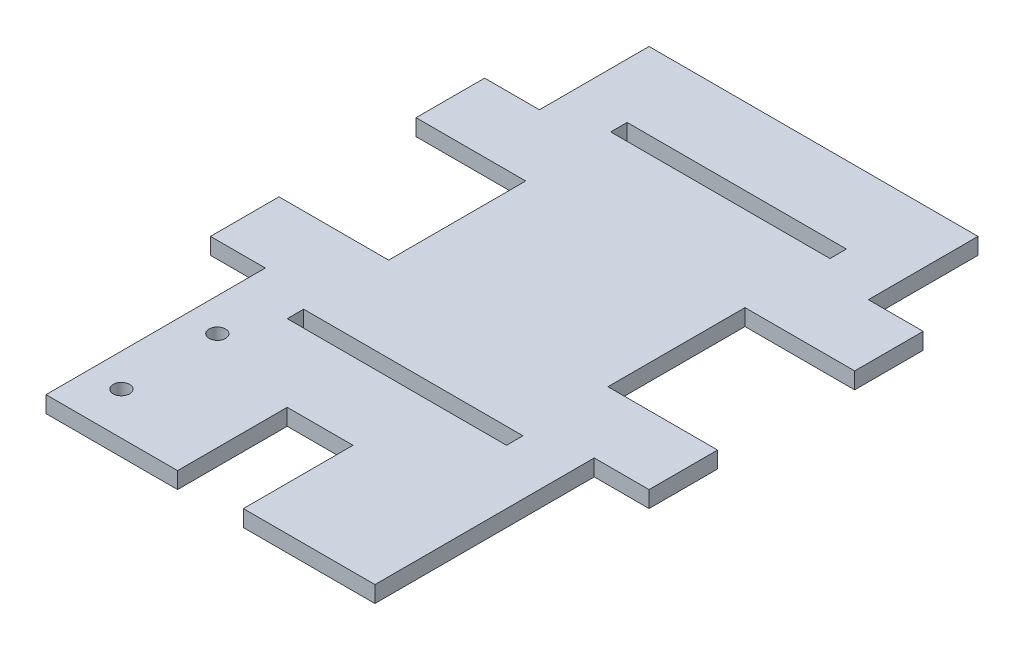
SolidWorks part; units mm, degrees
ref_plane "Front Plane" through (0, 0, 0) normal (0, 0, 1) x (1, 0, 0)
ref_plane "Top Plane" through (0, 0, 0) normal (0, 1, 0) x (1, 0, 0)
ref_plane "Right Plane" through (0, 0, 0) normal (1, 0, 0) x (0, 0, -1)
sketch "Sketch1" plane through (0, 0, 0) normal (0, 1, 0) x (1, 0, 0)
  line L0 (0, 25) -> (80, 25)
  line L1 (0, 0) -> (80, 0)
  line L2 (0, 0) -> (0, 50)
  line L3 (0, 50) -> (80, 50)
  line L4 (80, 0) -> (80, 50)
  line L5 (10, 0) -> (70, 0)
  line L6 (10, 0) -> (10, -40)
  line L7 (10, -40) -> (70, -40)
  line L8 (70, 0) -> (70, -40)
  line L9 (20, -3) -> (60, -3)
  line L10 (20, -3) -> (20, -6)
  line L11 (20, -6) -> (60, -6)
  line L12 (60, -3) -> (60, -6)
  line L13 (20, 53) -> (20, 56)
  line L14 (60, 53) -> (60, 56)
  line L15 (20, 53) -> (60, 53)
  line L16 (20, 56) -> (60, 56)
  line L17 (70, 50) -> (70, 90)
  line L18 (10, 90) -> (70, 90)
  line L19 (10, 50) -> (10, 90)
  line L20 (0, 50) -> (80, 50)
  line L21 (0, 50) -> (0, 25)
  line L22 (0, 37.5) -> (20, 37.5)
  line L23 (20, 37.5) -> (20, 12.5)
  line L24 (20, 25) -> (60, 25)
  line L25 (60, 12.5) -> (60, 37.5)
  line L26 (60, 37.5) -> (80, 37.5)
  line L27 (60, 12.5) -> (80, 12.5)
  line L28 (0, 12.5) -> (20, 12.5)
  point P13 (40, -3)
  point P14 (40, 0)
  dimension "D1" = 80
  dimension "D2" = 50
  dimension "D3" = 10
  dimension "D4" = 10
  dimension "D5" = 40
  dimension "D6" = 3
  dimension "D7" = 3
  dimension "D8" = 40
  dimension "D9" = 0
extrude "Boss-Extrude1" add sketch "Sketch1" along normal blind 3 contours L1 L4 L3 L2 | L8 L1 L6 L7 L9 L12 L11 L10 | L25 L26 L4 L3 L21 L22 L23 L0 | L19 L3 L17 L18 L13 L16 L14 L15
sketch "Sketch2" plane through (0, 0, 0) normal (0, 1, 0) x (1, 0, 0)
  line L0 (40, -40) -> (40, -6)
  line L1 (10, -40) -> (70, -40) construction
  line L2 (20, -6) -> (60, -6) construction
  line L3 (40, -23) -> (31.25, -23)
  circle A0 centre (31.25, -23) radius 1.25
  circle A1 centre (48.75, -23) radius 1.25
  dimension "D2" = 2.5
  dimension "D1" = 8.75
extrude "Cut-Extrude1" [suppressed] cut sketch "Sketch2" along normal blind 10
sketch "Sketch3" plane through (0, 0, 0) normal (0, 1, 0) x (1, 0, 0)
  line L0 (40, -40) -> (40, -6)
  line L1 (10, -40) -> (70, -40) construction
  line L2 (20, -6) -> (60, -6) construction
  line L4 (10, 0) -> (10, -40) construction
  line L6 (70, 50) -> (70, 90) construction
  line L7 (34, -40) -> (34, -20)
  line L8 (34, -20) -> (46, -20)
  line L9 (10, -32) -> (10, -40)
  line L11 (34, -40) -> (46, -40)
  line L12 (46, -40) -> (46, -20)
  line L14 (70, -32) -> (70, -40)
  line L15 (70, -40) -> (54, -40)
  line L17 (10, 90) -> (70, 90)
  line L18 (34, -13.9996) -> (34, -40)
  line L19 (26, -40) -> (34, -40)
  line L20 (26, -40) -> (34, -40)
  line L21 (54, -40) -> (46, -40)
  line L22 (10, 90) -> (10, 70)
  line L23 (10, 70) -> (70, 70)
  line L24 (70, 90) -> (70, 70)
  line L25 (10, -40) -> (16, -40)
  line L26 (16, -40) -> (16, -32.25)
  line L27 (16, -32.25) -> (16, -14.75)
  circle A0 centre (16, -32.25) radius 1.5
  circle A1 centre (16, -14.75) radius 1.5
  point P18 (40, -20)
  dimension "D7" = 3
  dimension "D8" = 3
  dimension "D1" = 6
  dimension "D2" = 6
  dimension "D3" = 7.75
  dimension "D4" = 20
  dimension "D5" = 20
  dimension "D6" = 17.5
extrude "Cut-Extrude2" cut sketch "Sketch3" along normal blind 10
